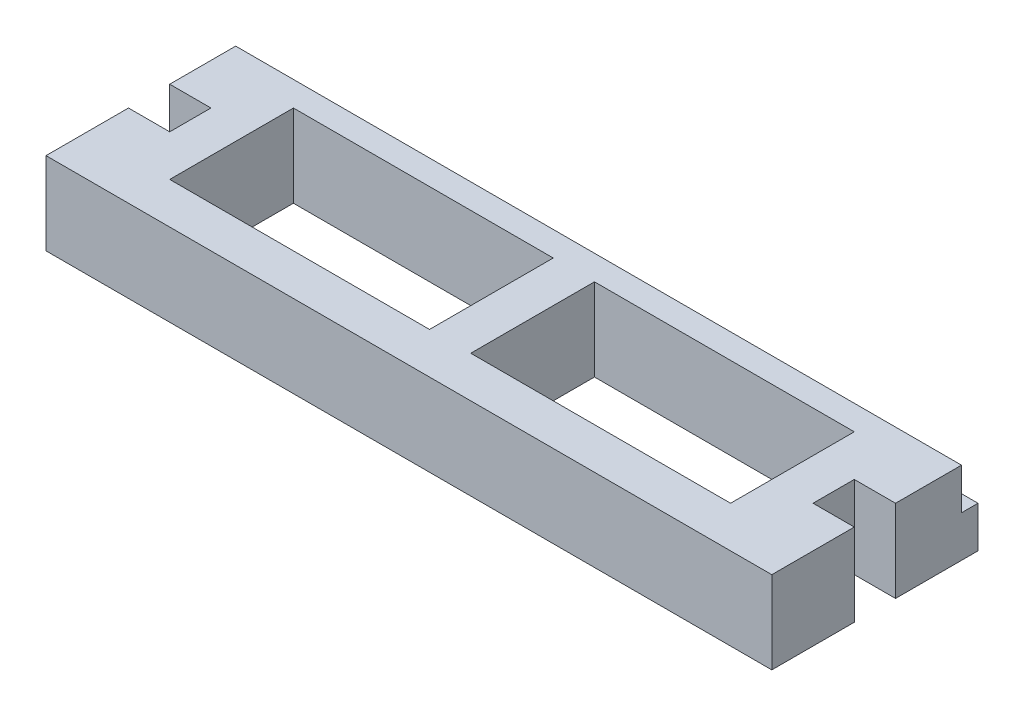
SolidWorks part; units mm, degrees
ref_plane "Front Plane" through (0, 0, 0) normal (0, 0, 1) x (1, 0, 0)
ref_plane "Top Plane" through (0, 0, 0) normal (0, 1, 0) x (1, 0, 0)
ref_plane "Right Plane" through (0, 0, 0) normal (1, 0, 0) x (0, 0, -1)
sketch "Sketch1" plane through (0, 0, 0) normal (0, 1, 0) x (1, 0, 0)
  line L1 (-49, 12.5) -> (49, 12.5)
  line L2 (-49, 12.5) -> (-49, -12.5)
  line L3 (-49, -12.5) -> (49, -12.5)
  line L4 (49, 12.5) -> (49, -12.5)
  line L5 (-49, 12.5) -> (49, -12.5) construction
  line L6 (-49, -12.5) -> (49, 12.5) construction
  point P0 (0, 0)
extrude "Boss-Extrude1" add sketch "Sketch1" along normal blind 10
sketch "Sketch2" plane through (0, 10, 0) normal (0, 1, 0) x (1, 0, 0)
  line L5 (-49, 0) -> (-34, 0)
  line L6 (-49, 12.5) -> (-49, -12.5) construction
  line L7 (34, 7.5) -> (34, -7.5)
  line L16 (-34, -7.5) -> (-34, 7.5)
  line L19 (49, 0) -> (34, 0)
  line L20 (34, -7.5) -> (2.5, -7.5)
  line L25 (49, -12.5) -> (49, 12.5) construction
  line L26 (34, 7.5) -> (2.5, 7.5)
  line L27 (-2.5, 7.5) -> (-34, 7.5)
  line L28 (-2.5, -7.5) -> (-34, -7.5)
  line L29 (2.5, 2.404) -> (2.5, 7.5)
  line L30 (2.5, 2.404) -> (2.5, -7.5)
  line L31 (-2.5, 2.404) -> (-2.5, 7.5)
  line L32 (-2.5, 2.404) -> (-2.5, -7.5)
  line L33 (-18.25, 7.5) -> (-18.25, 12.5)
  line L34 (49, 12.5) -> (-49, 12.5) construction
  point P0 (0, 0)
  point P10 (0, 0)
  point P11 (0, 0)
extrude "Cut-Extrude4" cut sketch "Sketch2" against normal blind 10 contours L32 L31 L27 L16 L28 | L29 L30 L20 L7 L26
sketch "Sketch4" plane through (-49, 0, 0) normal (-1, 0, 0) x (0, 0, 1)
  line L1 (-12.5, 0) -> (12.5, 0)
  line L2 (-12.5, 0) -> (-12.5, 10)
  line L3 (-12.5, 10) -> (12.5, 10)
  line L4 (12.5, 0) -> (12.5, 10)
extrude "Cut-Extrude6" cut sketch "Sketch4" against normal blind 5
sketch "Sketch5" plane through (49, 0, 0) normal (1, 0, 0) x (0, 0, -1)
  line L1 (12.5, 10) -> (-12.5, 10)
  line L2 (12.5, 10) -> (12.5, 0)
  line L3 (12.5, 0) -> (-12.5, 0)
  line L4 (-12.5, 10) -> (-12.5, 0)
extrude "Cut-Extrude7" cut sketch "Sketch5" against normal blind 5
sketch "Sketch6" plane through (44, 0, 0) normal (1, 0, 0) x (0, 0, -1)
  line L1 (12.5, 10) -> (-12.5, 10) construction
  line L2 (-2.5, 10) -> (2.5, 10)
  line L3 (2.5, 10) -> (2.5, 0)
  line L4 (-12.5, 0) -> (12.5, 0) construction
  line L5 (2.5, 0) -> (-2.5, 0)
  line L6 (-2.5, 10) -> (-2.5, 0)
extrude "Cut-Extrude8" cut sketch "Sketch6" against normal blind 5
sketch "Sketch7" plane through (-44, 0, 0) normal (-1, 0, 0) x (0, 0, 1)
  line L1 (-2.5, 0) -> (2.5, 0)
  line L2 (-2.5, 0) -> (-2.5, 10)
  line L3 (-2.5, 10) -> (2.5, 10)
  line L4 (2.5, 0) -> (2.5, 10)
extrude "Cut-Extrude9" cut sketch "Sketch7" against normal blind 5
sketch "Sketch8" plane through (0, 0, -12.5) normal (0, 0, -1) x (-1, 0, 0)
  line L0 (44, 10) -> (44, 0) construction
  line L1 (-44, 10) -> (44, 10)
  line L2 (-44, 10) -> (-44, 5)
  line L3 (-44, 5) -> (44, 5)
  line L4 (44, 10) -> (44, 5)
extrude "Cut-Extrude10" cut sketch "Sketch8" against normal blind 2
